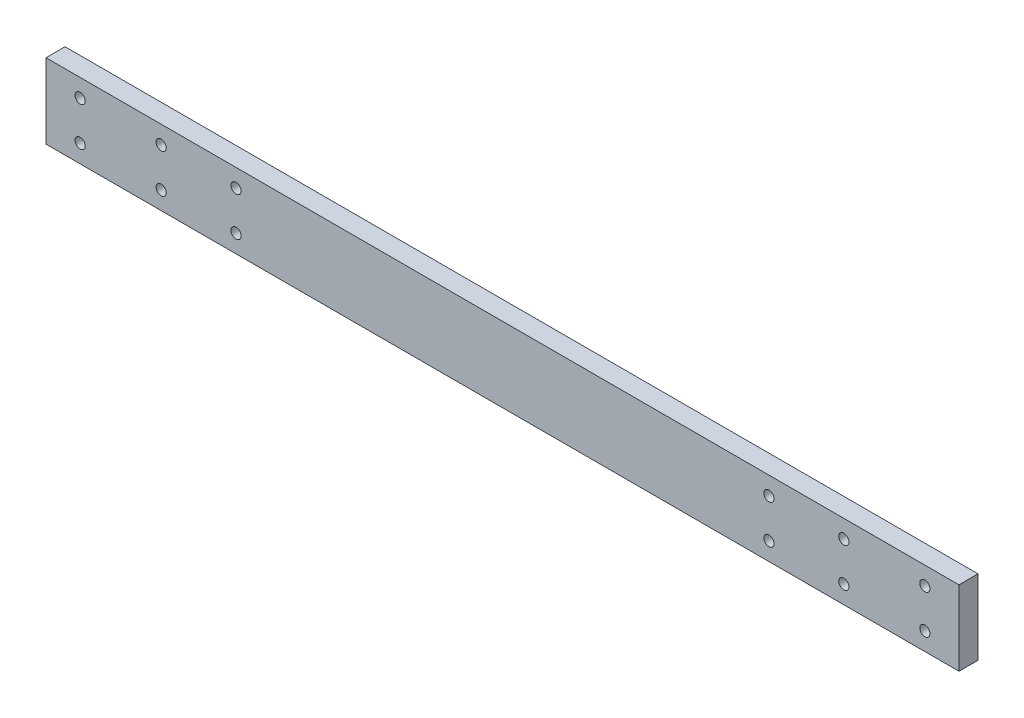
SolidWorks part; units mm, degrees
material "Balsa"
ref_plane "Front Plane" through (0, 0, 0) normal (0, 0, 1) x (1, 0, 0)
ref_plane "Top Plane" through (0, 0, 0) normal (0, 1, 0) x (1, 0, 0)
ref_plane "Right Plane" through (0, 0, 0) normal (1, 0, 0) x (0, 0, -1)
sketch "Sketch1" plane through (0, 0, 0) normal (0, 0, 1) x (1, 0, 0)
  line L1 (-40.7762, 235.9236) -> (264.0238, 235.9236)
  line L2 (-40.7762, 235.9236) -> (-40.7762, 210.9236)
  line L3 (-40.7762, 210.9236) -> (264.0238, 210.9236)
  line L4 (-40.7762, 235.9236) -> (-40.7762, -68.8764)
  line L5 (-40.7762, -68.8764) -> (264.0238, -68.8764)
  line L6 (264.0238, -68.8764) -> (264.0238, 235.9236)
  line L7 (264.0238, 235.9236) -> (-40.7762, 235.9236)
  line L11 (264.0238, 235.9236) -> (-40.7762, 235.9236)
  line L12 (264.0238, 235.9236) -> (264.0238, 210.9236)
  dimension "D1" = 0
extrude "Boss-Extrude1" add sketch "Sketch1" along normal blind 6.35 contours L12 L1 L2 L3
sketch "Sketch2" plane through (0, 0, 6.35) normal (0, 0, 1) x (1, 0, 0)
  circle A0 centre (-2.3262, 229.9236) radius 1.7 construction
  circle A1 centre (-2.3262, 216.9236) radius 1.7 construction
  circle A2 centre (-29.3762, 229.9236) radius 1.7 construction
  circle A3 centre (-29.3762, 216.9236) radius 1.7 construction
  circle A4 centre (-2.3262, 229.9236) radius 1.7
  circle A5 centre (-2.3262, 216.9236) radius 1.7
  circle A6 centre (-29.3762, 229.9236) radius 1.7
  circle A7 centre (-29.3762, 216.9236) radius 1.7
  circle A8 centre (252.6238, 229.9236) radius 1.7 construction
  circle A9 centre (252.6238, 216.9236) radius 1.7 construction
  circle A10 centre (225.5738, 229.9236) radius 1.7 construction
  circle A11 centre (225.5738, 216.9236) radius 1.7 construction
  circle A12 centre (252.6238, 229.9236) radius 1.7
  circle A13 centre (252.6238, 216.9236) radius 1.7
  circle A14 centre (225.5738, 229.9236) radius 1.7
  circle A15 centre (225.5738, 216.9236) radius 1.7
extrude "Cut-Extrude1" cut sketch "Sketch2" against normal blind 30
sketch "Sketch3" plane through (0, 0, 6.35) normal (0, 0, 1) x (1, 0, 0)
  circle A0 centre (22.6738, 216.9236) radius 1.7 construction
  circle A1 centre (22.6738, 229.9236) radius 1.7 construction
  circle A2 centre (22.6738, 216.9236) radius 1.7
  circle A3 centre (22.6738, 229.9236) radius 1.7
  circle A4 centre (200.5738, 216.9236) radius 1.7 construction
  circle A5 centre (200.5738, 229.9236) radius 1.7 construction
  circle A6 centre (200.5738, 216.9236) radius 1.7
  circle A7 centre (200.5738, 229.9236) radius 1.7
extrude "Cut-Extrude2" cut sketch "Sketch3" against normal blind 21
